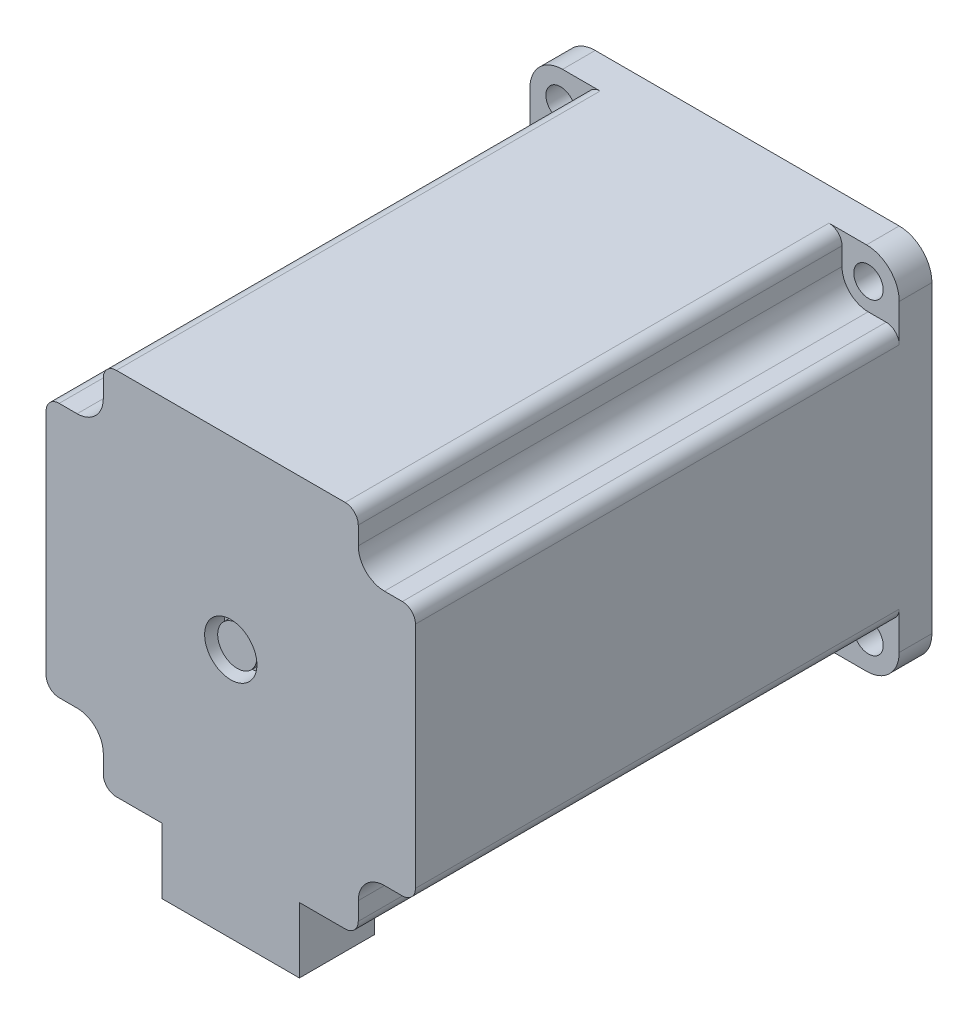
SolidWorks part; units mm, degrees
material "SKD11淬火HRC56-60"
ref_plane "前基準面" through (0, 0, 0) normal (0, 0, 1) x (1, 0, 0)
ref_plane "上基準面" through (0, 0, 0) normal (0, 1, 0) x (1, 0, 0)
ref_plane "右基準面" through (0, 0, 0) normal (1, 0, 0) x (0, 0, -1)
sketch "草图1" plane through (0, 0, 0) normal (0, 0, 1) x (1, 0, 0)
  line L1 (0, 0) -> (56.5, 0)
  line L2 (0, 0) -> (0, 56.5)
  line L3 (0, 56.5) -> (56.5, 56.5)
  line L4 (56.5, 0) -> (56.5, 56.5)
  dimension "D1" = 56.5
extrude "凸台-拉伸1" add sketch "草图1" along normal blind 79
fillet "圆角1" radius 5 4 edges at (56.5, 0, 39.5) (0, 0, 39.5) (0, 56.5, 39.5) (56.5, 56.5, 39.5)
sketch "草图2" plane through (0, 0, 79) normal (0, 0, 1) x (1, 0, 0)
  line L0 (28.25, 56.5) -> (28.25, 0) construction
  line L1 (-19.1874, 65.2751) -> (8.75, 65.2751)
  line L2 (-19.1874, 65.2751) -> (-19.1874, 47.75)
  line L3 (-19.1874, 47.75) -> (8.75, 47.75)
  line L4 (8.75, 65.2751) -> (8.75, 47.75)
  line L5 (51.5, 56.5) -> (5, 56.5) construction
  line L6 (5, 0) -> (51.5, 0) construction
  line L7 (0, 28.25) -> (56.5, 28.25) construction
  line L8 (0, 51.5) -> (0, 5) construction
  line L9 (56.5, 5) -> (56.5, 51.5) construction
  line L10 (47.75, 65.2751) -> (47.75, 47.75)
  line L11 (75.6874, 47.75) -> (47.75, 47.75)
  line L12 (75.6874, 65.2751) -> (75.6874, 47.75)
  line L13 (75.6874, 65.2751) -> (47.75, 65.2751)
  line L14 (75.6874, -8.7751) -> (47.75, -8.7751)
  line L15 (75.6874, -8.7751) -> (75.6874, 8.75)
  line L16 (75.6874, 8.75) -> (47.75, 8.75)
  line L17 (47.75, -8.7751) -> (47.75, 8.75)
  line L18 (8.75, -8.7751) -> (8.75, 8.75)
  line L19 (-19.1874, 8.75) -> (8.75, 8.75)
  line L20 (-19.1874, -8.7751) -> (-19.1874, 8.75)
  line L21 (-19.1874, -8.7751) -> (8.75, -8.7751)
  dimension "D1" = 39
  dimension "D2" = 39
extrude "切除-拉伸1" cut sketch "草图2" against normal blind 74
fillet "圆角2" radius 4 4 edges at (8.75, 8.75, 42) (47.75, 8.75, 42) (47.75, 47.75, 42) (8.75, 47.75, 42)
fillet "圆角3" radius 2 8 edges at (0, 8.75, 42) (8.75, 0, 42) (47.75, 0, 42) (56.5, 8.75, 42) (56.5, 47.75, 42) (47.75, 56.5, 42) (8.75, 56.5, 42) (0, 47.75, 42)
sketch "草图3" plane through (0, 0, 0) normal (0, 0, -1) x (-1, 0, 0)
  line L0 (-56.5, 28.25) -> (0, 28.25) construction
  line L1 (-56.5, 5) -> (-56.5, 51.5) construction
  line L2 (0, 51.5) -> (0, 5) construction
  circle A0 centre (-28.25, 28.25) radius 19
  dimension "D1" = 38
extrude "凸台-拉伸2" add sketch "草图3" along normal blind 1.5
sketch "草图4" plane through (0, 0, 79) normal (0, 0, 1) x (1, 0, 0)
  line L0 (56.5, 28.25) -> (0, 28.25) construction
  line L1 (56.5, 10.75) -> (56.5, 45.75) construction
  line L2 (0, 45.75) -> (0, 10.75) construction
  circle A0 centre (28.25, 28.25) radius 4
  dimension "D1" = 8
extrude "切除-拉伸2" cut sketch "草图4" against normal blind 3
sketch "草图5" plane through (0, 0, 76) normal (0, 0, 1) x (1, 0, 0)
  circle A0 centre (28.25, 28.25) radius 3
  dimension "D1" = 6
extrude "凸台-拉伸3" add sketch "草图5" along normal blind 2
sketch "草图6" plane through (0, 0, -1.5) normal (0, 0, -1) x (-1, 0, 0)
  circle A0 centre (-28.25, 28.25) radius 3.175
  dimension "D1" = 6.35
extrude "凸台-拉伸4" add sketch "草图6" along normal blind 19
sketch "草图7" plane through (0, 0, 0) normal (0, 0, -1) x (-1, 0, 0)
  line L0 (-56.5, 28.25) -> (0, 28.25) construction
  line L1 (-56.5, 5) -> (-56.5, 51.5) construction
  line L2 (0, 51.5) -> (0, 5) construction
  line L3 (-28.25, 56.5) -> (-28.25, 0) construction
  line L4 (-51.5, 56.5) -> (-5, 56.5) construction
  line L5 (-5, 0) -> (-51.5, 0) construction
  circle A0 centre (-51.8, 4.7) radius 2.25
  circle A1 centre (-4.7, 4.7) radius 2.25
  circle A2 centre (-4.7, 51.8) radius 2.25
  circle A3 centre (-51.8, 51.8) radius 2.25
  dimension "D1" = 4.5
  dimension "D2" = 47.1
  dimension "D3" = 47.1
extrude "切除-拉伸3" cut sketch "草图7" against normal blind 21
sketch "草图8" plane through (0, 0, 0) normal (0, -1, 0) x (1, 0, 0)
  line L0 (10.75, 79) -> (45.75, 79) construction
  line L1 (17.75, 79) -> (38.75, 79)
  line L2 (17.75, 79) -> (17.75, 67.5)
  line L3 (17.75, 67.5) -> (38.75, 67.5)
  line L4 (38.75, 79) -> (38.75, 67.5)
  line L5 (28.25, 79) -> (28.25, 42.9487) construction
  dimension "D1" = 21
  dimension "D2" = 11.5
extrude "凸台-拉伸5" add sketch "草图8" along normal blind 10
sketch "草图9" plane through (0, -10, 0) normal (0, -1, 0) x (1, 0, 0)
  line L0 (28.25, 67.5) -> (28.25, 79) construction
  line L1 (34.25, 71.5) -> (22.25, 71.5)
  line L2 (34.25, 71.5) -> (34.25, 68.5)
  line L3 (34.25, 68.5) -> (22.25, 68.5)
  line L4 (22.25, 71.5) -> (22.25, 68.5)
  line L5 (17.75, 67.5) -> (38.75, 67.5) construction
  line L6 (38.75, 79) -> (17.75, 79) construction
  dimension "D1" = 3
  dimension "D2" = 1
  dimension "D3" = 12
extrude "切除-拉伸4" cut sketch "草图9" against normal blind 5
sketch "草图10" plane through (0, 0, 0) normal (1, 0, 0) x (0, 0, -1)
  line L0 (20.5, 25.075) -> (20.5, 31.425) construction
  line L1 (5.5, 22.4524) -> (20.5, 22.4524)
  line L2 (5.5, 22.4524) -> (5.5, 25.925)
  line L3 (5.5, 25.925) -> (20.5, 25.925)
  line L4 (20.5, 22.4524) -> (20.5, 25.925)
  line L6 (20.5, 31.425) -> (1.5, 31.425) construction
  dimension "D1" = 5.5
  dimension "D2" = 15
extrude "切除-拉伸6" cut sketch "草图10" along normal through all
